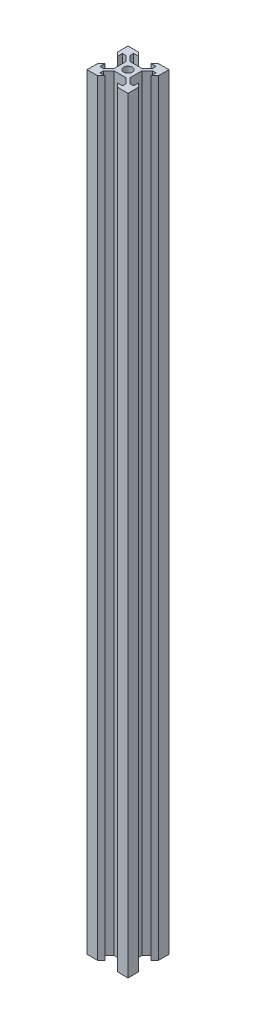
SolidWorks part; units mm, degrees
ref_plane "Front Plane" through (0, 0, 0) normal (0, 0, 1) x (1, 0, 0)
ref_plane "Top Plane" through (0, 0, 0) normal (0, 1, 0) x (1, 0, 0)
ref_plane "Right Plane" through (0, 0, 0) normal (1, 0, 0) x (0, 0, -1)
sketch "Sketch1" plane through (0, 0, 0) normal (0, 1, 0) x (1, 0, 0)
  line L0 (3.9007, 2.84) -> (2.84, 3.9007) construction
  line L1 (-10, -10) -> (10, -10) construction
  line L2 (-10, -10) -> (-10, 10) construction
  line L3 (-10, 10) -> (10, 10) construction
  line L4 (10, -10) -> (10, 10) construction
  line L5 (-10, -10) -> (10, 10) construction
  line L6 (-10, 10) -> (10, -10) construction
  line L7 (-2.84, -2.84) -> (2.84, -2.84) construction
  line L8 (-2.84, -2.84) -> (-2.84, 2.84) construction
  line L9 (-2.84, 2.84) -> (2.84, 2.84) construction
  line L10 (2.84, -2.84) -> (2.84, 2.84) construction
  line L11 (-2.84, -2.84) -> (2.84, 2.84) construction
  line L12 (-2.84, 2.84) -> (2.84, -2.84) construction
  line L13 (2.84, -3.9007) -> (3.9007, -2.84) construction
  line L14 (-3.9007, -2.84) -> (-2.84, -3.9007) construction
  line L15 (-2.84, 3.9007) -> (-3.9007, 2.84) construction
  line L16 (-3.1, 10) -> (3.1, 10) construction
  line L17 (-3.1, 10) -> (-3.1, 8.2) construction
  line L18 (-3.1, 8.2) -> (-4.9, 10)
  line L19 (3.1, 8.2) -> (3.1, 10) construction
  line L20 (-3.1, 8.2) -> (-8.2, 8.2) construction
  line L21 (-2.84, 3.9007) -> (-7.1393, 8.2) construction
  line L22 (-5.4993, 8.2) -> (-5.4993, 6.56)
  line L23 (-4.9, 10) -> (-10, 10)
  line L24 (-3.9007, -3.9007) -> (3.9007, -3.9007) construction
  line L25 (-3.9007, -3.9007) -> (-3.9007, 3.9007) construction
  line L26 (-3.9007, 3.9007) -> (3.9007, 3.9007) construction
  line L27 (3.9007, -3.9007) -> (3.9007, 3.9007) construction
  line L28 (-3.9007, -3.9007) -> (3.9007, 3.9007) construction
  line L29 (-3.9007, 3.9007) -> (3.9007, -3.9007) construction
  line L30 (-5.4993, 6.56) -> (-2.84, 3.9007)
  line L31 (-2.84, 3.9007) -> (0, 3.9007)
  line L32 (-5.4993, 8.2) -> (-3.1, 8.2)
  line L33 (-3.9007, 2.84) -> (-3.9007, 0)
  line L34 (-6.56, 5.4993) -> (-3.9007, 2.84)
  line L35 (-8.2, 5.4993) -> (-6.56, 5.4993)
  line L36 (-8.2, 5.4993) -> (-8.2, 3.1)
  line L37 (-8.2, 3.1) -> (-10, 4.9)
  line L38 (-10, 4.9) -> (-10, 10)
  line L39 (2.84, 3.9007) -> (0, 3.9007)
  line L40 (5.4993, 6.56) -> (2.84, 3.9007)
  line L41 (5.4993, 8.2) -> (5.4993, 6.56)
  line L42 (5.4993, 8.2) -> (3.1, 8.2)
  line L43 (3.1, 8.2) -> (4.9, 10)
  line L44 (4.9, 10) -> (10, 10)
  line L45 (10, 4.9) -> (10, 10)
  line L46 (8.2, 3.1) -> (10, 4.9)
  line L47 (8.2, 5.4993) -> (8.2, 3.1)
  line L48 (8.2, 5.4993) -> (6.56, 5.4993)
  line L49 (6.56, 5.4993) -> (3.9007, 2.84)
  line L50 (3.9007, 2.84) -> (3.9007, 0)
  line L51 (3.9007, -2.84) -> (3.9007, 0)
  line L52 (6.56, -5.4993) -> (3.9007, -2.84)
  line L53 (8.2, -5.4993) -> (6.56, -5.4993)
  line L54 (8.2, -5.4993) -> (8.2, -3.1)
  line L55 (8.2, -3.1) -> (10, -4.9)
  line L56 (10, -4.9) -> (10, -10)
  line L57 (4.9, -10) -> (10, -10)
  line L58 (3.1, -8.2) -> (4.9, -10)
  line L59 (5.4993, -8.2) -> (3.1, -8.2)
  line L60 (5.4993, -8.2) -> (5.4993, -6.56)
  line L61 (5.4993, -6.56) -> (2.84, -3.9007)
  line L62 (2.84, -3.9007) -> (0, -3.9007)
  line L63 (-2.84, -3.9007) -> (0, -3.9007)
  line L64 (-5.4993, -6.56) -> (-2.84, -3.9007)
  line L65 (-5.4993, -8.2) -> (-5.4993, -6.56)
  line L66 (-5.4993, -8.2) -> (-3.1, -8.2)
  line L67 (-3.1, -8.2) -> (-4.9, -10)
  line L68 (-4.9, -10) -> (-10, -10)
  line L69 (-10, -4.9) -> (-10, -10)
  line L70 (-8.2, -3.1) -> (-10, -4.9)
  line L71 (-8.2, -5.4993) -> (-8.2, -3.1)
  line L72 (-8.2, -5.4993) -> (-6.56, -5.4993)
  line L73 (-6.56, -5.4993) -> (-3.9007, -2.84)
  line L74 (-3.9007, -2.84) -> (-3.9007, 0)
  circle A0 centre (0, 0) radius 2.1
  circle A1 centre (0, 0) radius 2.1
  circle A2 centre (0, 0) radius 2.1
  circle A3 centre (0, 0) radius 2.1
  point P0 (0, 0)
  point P15 (3.3703, 3.3703)
  point P27 (0, 0)
  point P28 (0, 10)
  point P87 (0, 0)
  dimension "D2" = 4.2
  dimension "D1" = 20
  dimension "D3" = 5.68
  dimension "D4" = 1.5
  dimension "D6" = 6.2
  dimension "D7" = 1.8
  dimension "D8" = 45
  dimension "D9" = 1.64
  dimension "D10" = 4
  dimension "D11" = 90
  dimension "D12" = 1.64
  dimension "D13" = 20
  dimension "D14" = 1.5
  dimension "D15" = 5.68
  dimension "D16" = 6.2
  dimension "D17" = 1.8
  dimension "D5" = 4
extrude "Boss-Extrude1" add sketch "Sketch1" along normal blind 374.1657 contours L74 L73 L72 L71 L70 L69 L68 L67 L66 L65 L64 L63 L62 L61 L60 L59 L58 L57 L56 L55 L54 L53 L52 L51 L50 L49 L48 L47 L46 L45 L44 L43 L42 L41 L40 L39 L31 L30 L22 L32 L18 L23 L38 L37 L36 L35 L34 L33 A0
